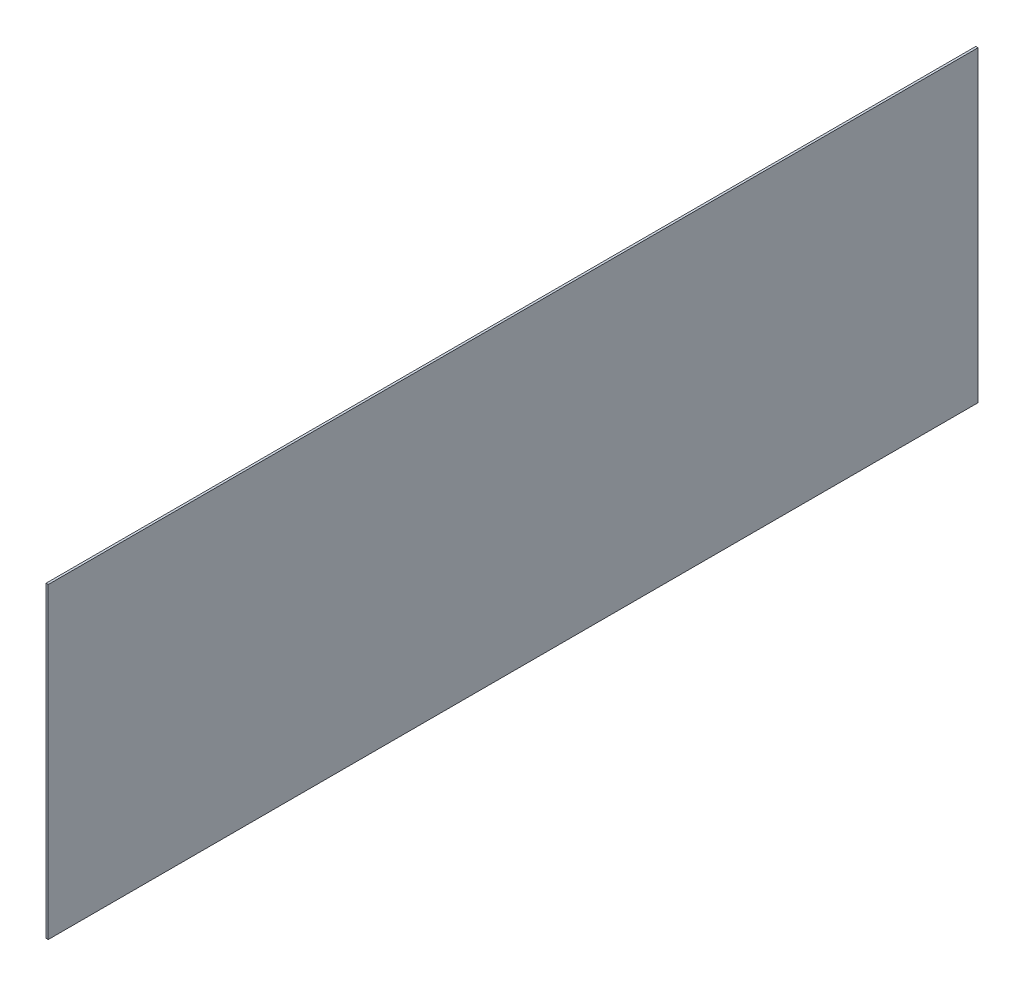
SolidWorks part; units mm, degrees
material "Custom Plastic"
ref_plane "X-Y Datum" through (0, 0, 0) normal (0, 0, 1) x (1, 0, 0)
ref_plane "X-Z Datum" through (0, 0, 0) normal (0, 1, 0) x (1, 0, 0)
ref_plane "Y-Z Datum" through (0, 0, 0) normal (1, 0, 0) x (0, 0, -1)
sketch "Sketch1" plane through (0, 0, 0) normal (1, 0, 0) x (0, 0, -1)
  line L1 (0, 0) -> (414.644, 0)
  line L2 (0, 0) -> (0, 137.1237)
  line L3 (0, 137.1237) -> (414.644, 137.1237)
  line L4 (414.644, 0) -> (414.644, 137.1237)
extrude "Boss-Extrude1" add sketch "Sketch1" along normal blind 1 contours L3 L4 L1 L2
